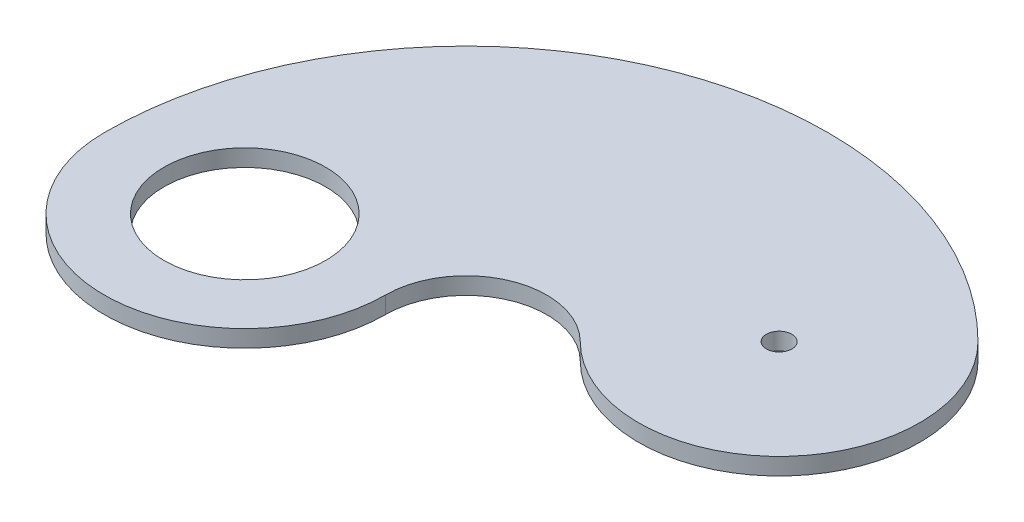
SolidWorks part; units mm, degrees
material "Oak"
ref_plane "Front Plane" through (0, 0, 0) normal (0, 0, 1) x (1, 0, 0)
ref_plane "Top Plane" through (0, 0, 0) normal (0, 1, 0) x (1, 0, 0)
ref_plane "Right Plane" through (0, 0, 0) normal (1, 0, 0) x (0, 0, -1)
sketch "Sketch1" plane through (0, 0, 0) normal (0, 1, 0) x (1, 0, 0)
  circle A0 centre (0, 0) radius 135
  dimension "D1" = 270
extrude "Boss-Extrude1" add sketch "Sketch1" along normal blind 6.35
sketch "Sketch2" plane through (0, 6.35, 0) normal (0, 1, 0) x (1, 0, 0)
  line L0 (0, 0) -> (-82.55, 0) construction
  line L1 (0, 0) -> (95.4594, 95.4594) construction
  line L2 (0, 0) -> (0, 135) construction
  arc A0 (-135, 0) -> (-30.1, 0) centre (-82.55, 0) ccw
  circle A1 centre (-82.55, 0) radius 30.1625
  circle A2 centre (0, 0) radius 135 construction
  arc A3 (95.4594, 95.4594) -> (-135, 0) centre (0, 0) ccw
  arc A4 (21.2839, 21.2839) -> (-30.1, 0) centre (0, 0) ccw
  arc A5 (21.2839, 21.2839) -> (95.4594, 95.4594) centre (58.3717, 58.3717) ccw
  circle M1 centre (0, 0) radius 135
  dimension "D1" = 60.325
  dimension "D2" = 82.55
  dimension "D4" = 45
extrude "Cut-Extrude1" cut sketch "Sketch2" against normal through all contours A5 A4 A0 M1 | A1
sketch "Sketch3" plane through (0, 6.35, 0) normal (0, 1, 0) x (1, 0, 0)
  line L0 (0, 0) -> (0, 135) construction
  line L1 (0, 0) -> (95.4594, 95.4594) construction
  arc A0 (95.4594, 95.4594) -> (-135, 0) centre (0, 0) ccw construction
  circle A1 centre (58.3717, 58.3717) radius 4.7625
  dimension "D1" = 9.525
  dimension "D3" = 82.55
  dimension "D2" = 45
extrude "Cut-Extrude2" cut sketch "Sketch3" against normal through all
